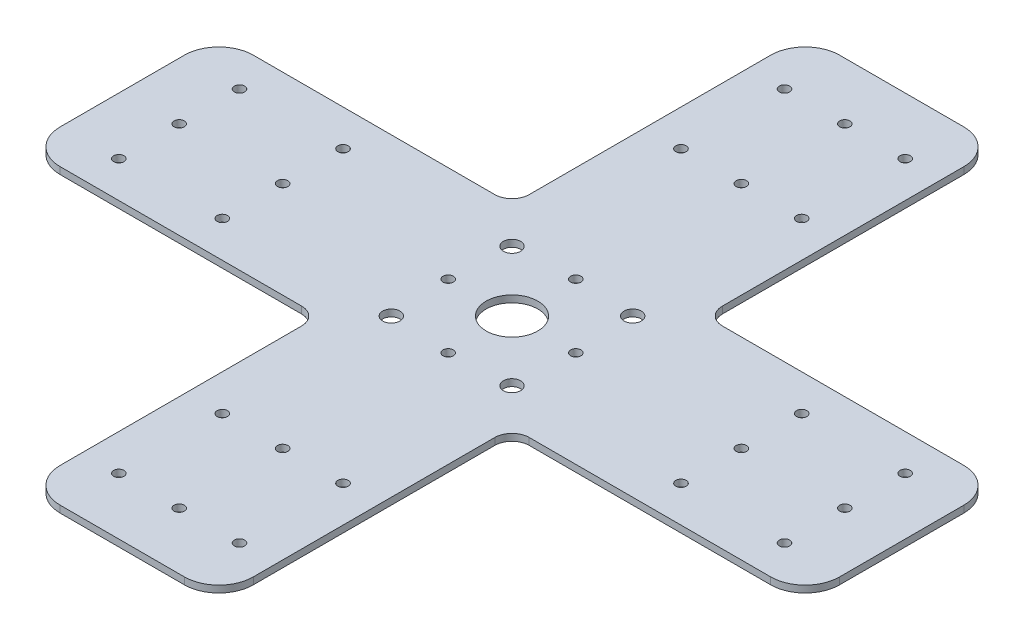
SolidWorks part; units mm, degrees
material "Thornel Mat VMA"
ref_plane "Front Plane" through (0, 0, 0) normal (0, 0, 1) x (1, 0, 0)
ref_plane "Top Plane" through (0, 0, 0) normal (0, 1, 0) x (1, 0, 0)
ref_plane "Right Plane" through (0, 0, 0) normal (1, 0, 0) x (0, 0, -1)
sketch "Sketch1" plane through (0, 0, 0) normal (0, 1, 0) x (1, 0, 0)
  line L0 (0, 28) -> (0, -28) construction
  line L5 (-113, 0) -> (113, 0) construction
  line L6 (28, 103) -> (28, -103)
  line L11 (-103, 28) -> (103, 28)
  line L12 (-113, 18) -> (-113, -18)
  line L13 (-103, -28) -> (103, -28)
  line L14 (113, 18) -> (113, -18)
  line L15 (18, 113) -> (-18, 113)
  line L16 (-28, 103) -> (-28, -103)
  line L17 (18, -113) -> (-18, -113)
  line L18 (28, 0) -> (-28, 0) construction
  line L19 (0, 113) -> (0, -113) construction
  arc A0 (103, 28) -> (113, 18) centre (103, 18) cw
  arc A1 (103, -28) -> (113, -18) centre (103, -18) ccw
  arc A2 (-113, -18) -> (-103, -28) centre (-103, -18) ccw
  arc A3 (-103, 28) -> (-113, 18) centre (-103, 18) ccw
  arc A4 (28, -103) -> (18, -113) centre (18, -103) cw
  arc A5 (-28, -103) -> (-18, -113) centre (-18, -103) ccw
  arc A6 (-18, 113) -> (-28, 103) centre (-18, 103) ccw
  arc A7 (28, 103) -> (18, 113) centre (18, 103) ccw
  arc A8 (-33, 28) -> (-28, 33) centre (-33, 33) ccw
  arc A9 (28, 33) -> (33, 28) centre (33, 33) ccw
  arc A10 (33, -28) -> (28, -33) centre (33, -33) ccw
  arc A11 (-28, -33) -> (-33, -28) centre (-33, -33) ccw
  point P20 (-113, -28)
  point P23 (-113, 28)
  point P38 (0, 0)
  point P51 (0, 0)
  dimension "D3" = 10
  dimension "D5" = 10
  dimension "D1" = 226
  dimension "D2" = 56
  dimension "D4" = 2
  dimension "D6" = 4
extrude "Boss-Extrude2" add sketch "Sketch1" along normal blind 2 contours L6 A7 L15 A6 L16 L11 | L11 L16 L13 L6 | L11 A3 L12 A2 L13 L16 | L16 A5 L17 A4 L6 L13 | L13 A1 L14 A0 L11 L6 | A10 L13 L6 | A11 L16 L13 | A8 L11 L16 | A9 L6 L11
sketch "Sketch2" plane through (0, 2, 0) normal (0, 1, 0) x (1, 0, 0)
  line L0 (113, 0) -> (-113, 0) construction
  line L1 (113, 18) -> (113, -18) construction
  line L2 (-113, 18) -> (-113, -18) construction
  line L3 (-96.5, 28) -> (-96.5, -28) construction
  line L4 (-103, 28) -> (-33, 28) construction
  line L5 (-103, -28) -> (-33, -28) construction
  line L6 (-66.5, 28) -> (-66.5, -28) construction
  line L7 (-113, 17.5) -> (-66.5, 17.5) construction
  circle A0 centre (0, 0) radius 7.5
  circle A1 centre (-96.5, 0) radius 1.5
  circle A2 centre (-66.5, 0) radius 1.5
  circle A3 centre (-96.5, 17.5) radius 1.5
  circle A4 centre (-66.5, 17.5) radius 1.5
  circle A5 centre (-66.5, -17.5) radius 1.5
  circle A6 centre (-96.5, -17.5) radius 1.5
  circle A7 centre (0, 96.5) radius 1.5
  circle A8 centre (0, 66.5) radius 1.5
  circle A9 centre (17.5, 96.5) radius 1.5
  circle A10 centre (17.5, 66.5) radius 1.5
  circle A11 centre (-17.5, 66.5) radius 1.5
  circle A12 centre (-17.5, 96.5) radius 1.5
  circle A13 centre (96.5, 0) radius 1.5
  circle A14 centre (66.5, 0) radius 1.5
  circle A15 centre (96.5, -17.5) radius 1.5
  circle A16 centre (66.5, -17.5) radius 1.5
  circle A17 centre (66.5, 17.5) radius 1.5
  circle A18 centre (96.5, 17.5) radius 1.5
  circle A19 centre (0, -96.5) radius 1.5
  circle A20 centre (0, -66.5) radius 1.5
  circle A21 centre (-17.5, -96.5) radius 1.5
  circle A22 centre (-17.5, -66.5) radius 1.5
  circle A23 centre (17.5, -66.5) radius 1.5
  circle A24 centre (17.5, -96.5) radius 1.5
  point P69 (0, 0)
  dimension "D1" = 15
  dimension "D5" = 3
  dimension "D2" = 30
  dimension "D3" = 16.5
  dimension "D4" = 17.5
  dimension "D6" = 4
extrude "Cut-Extrude1" cut sketch "Sketch2" against normal through all
sketch "Sketch3" plane through (0, 2, 0) normal (0, 1, 0) x (1, 0, 0)
  line L0 (-18.5, 0) -> (18.5, 0) construction
  line L3 (17.5, -17.5) -> (-17.5, -17.5) construction
  line L4 (17.5, -17.5) -> (17.5, 17.5) construction
  line L5 (17.5, 17.5) -> (-17.5, 17.5) construction
  line L6 (-17.5, -17.5) -> (-17.5, 17.5) construction
  line L7 (17.5, -17.5) -> (-17.5, 17.5) construction
  line L8 (17.5, 17.5) -> (-17.5, -17.5) construction
  circle A0 centre (-17.5, 17.5) radius 2.5
  circle A1 centre (17.5, 17.5) radius 2.5
  circle A2 centre (17.5, -17.5) radius 2.5
  circle A3 centre (-17.5, -17.5) radius 2.5
  circle A4 centre (-18.5, 0) radius 1.5
  circle A5 centre (18.5, 0) radius 1.5
  circle A6 centre (0, -18.5) radius 1.5
  circle A7 centre (0, 18.5) radius 1.5
  point P5 (0, 0)
  point P20 (0, 0)
  dimension "D2" = 5
  dimension "D4" = 3
  dimension "D1" = 35
  dimension "D3" = 37
  dimension "D5" = 2
extrude "Cut-Extrude2" cut sketch "Sketch3" against normal through all
